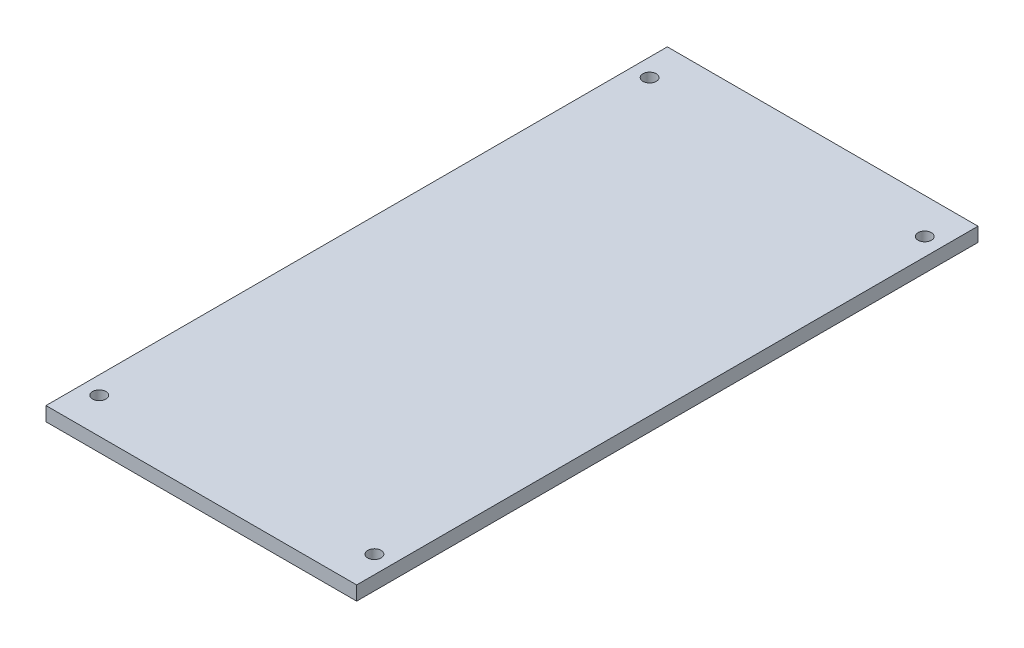
SolidWorks part; units mm, degrees
ref_plane "Front Plane" through (0, 0, 0) normal (0, 0, 1) x (1, 0, 0)
ref_plane "Top Plane" through (0, 0, 0) normal (0, 1, 0) x (1, 0, 0)
ref_plane "Right Plane" through (0, 0, 0) normal (1, 0, 0) x (0, 0, -1)
sketch "Sketch2" plane through (0, 0, 0) normal (0, 1, 0) x (1, 0, 0)
  line L0 (0, 70) -> (0, -70) construction
  line L1 (35, -70) -> (-35, -70)
  line L2 (35, -70) -> (35, 70)
  line L3 (35, 70) -> (-35, 70)
  line L4 (-35, -70) -> (-35, 70)
  line L5 (35, -70) -> (-35, 70) construction
  line L6 (35, 70) -> (-35, -70) construction
  line L7 (35, 0) -> (-35, 0) construction
  circle A0 centre (31, -62) radius 1.5
  circle A1 centre (31, 62) radius 1.5
  circle A2 centre (-31, 62) radius 1.5
  circle A3 centre (-31, -62) radius 1.5
  point P0 (0, 0)
  dimension "D4" = 3
  dimension "D1" = 70
  dimension "D2" = 140
  dimension "D3" = 4
  dimension "D5" = 8
extrude "Boss-Extrude1" add sketch "Sketch2" along normal blind 3.175
